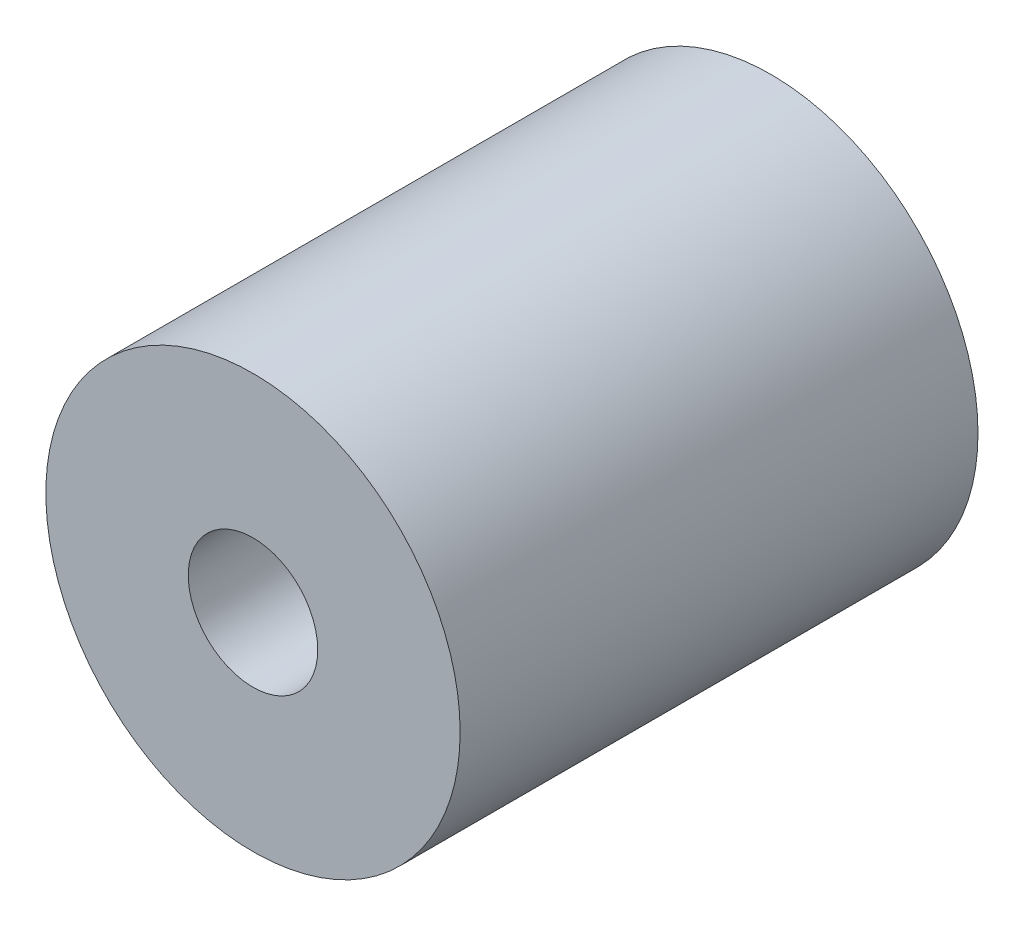
SolidWorks part; units mm, degrees
ref_plane "前视基准面" through (0, 0, 0) normal (0, 0, 1) x (1, 0, 0)
ref_plane "上视基准面" through (0, 0, 0) normal (0, 1, 0) x (1, 0, 0)
ref_plane "右视基准面" through (0, 0, 0) normal (1, 0, 0) x (0, 0, -1)
sketch "草图1" plane through (0, 0, 0) normal (0, 0, 1) x (1, 0, 0)
  circle A0 centre (0, 0) radius 4
  dimension "D1" = 8
extrude "凸台-拉伸1" add sketch "草图1" along normal blind 10
hole_wizard "M3x0.5 螺纹孔1" positions "草图3" profile "草图4" tap size "M3x0.5" standard "JIS" end condition through all
sketch "草图3" plane through (0, 0, 10) normal (0, 0, 1) x (1, 0, 0)
  point P1 (0, 0)
sketch "草图4" plane through (0, 0, 10) normal (1, 0, 0) x (0, -1, 0)
  line L0 (0, 0) -> (0, 10)
  line L1 (0, 10) -> (1.25, 10)
  line L2 (1.25, 10) -> (1.25, 0)
  line L5 (1.25, 0) -> (0, 0)
  line L11 (0, -6.35) -> (0, 107.95) construction
  dimension "通孔螺纹孔钻头直径" = 2.5
  dimension "通孔螺纹孔钻头深度" = 10
cosmetic thread "孔螺蚊线1" parameters "D2"=3
